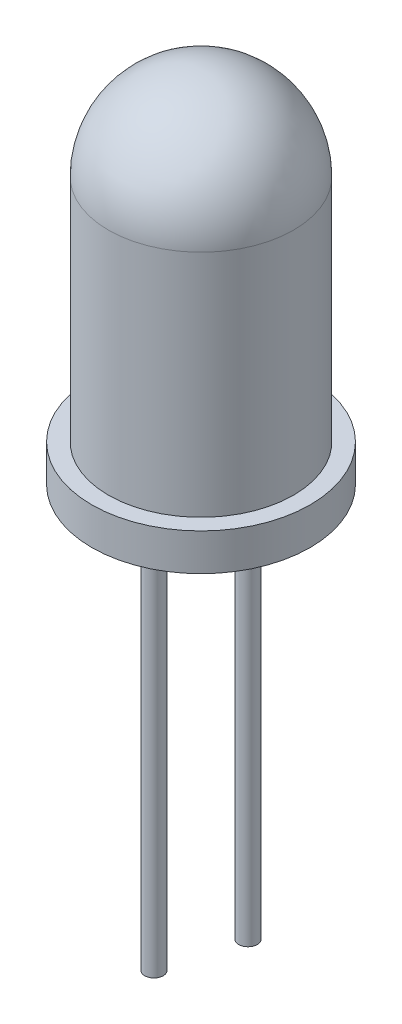
SolidWorks part; units mm, degrees
ref_plane "Front Plane" through (0, 0, 0) normal (0, 0, 1) x (1, 0, 0)
ref_plane "Top Plane" through (0, 0, 0) normal (0, 1, 0) x (1, 0, 0)
ref_plane "Right Plane" through (0, 0, 0) normal (1, 0, 0) x (0, 0, -1)
sketch "Sketch1" plane through (0, 0, 0) normal (0, 0, 1) x (1, 0, 0)
  line L0 (0, 0) -> (0, 9.7)
  line L1 (2.5, 7.2) -> (2.5, 1)
  line L2 (2.5, 1) -> (2.95, 1)
  line L3 (2.95, 1) -> (2.95, 0)
  line L4 (2.95, 0) -> (0, 0)
  arc A0 (0, 9.7) -> (2.5, 7.2) centre (0, 7.2) cw
  dimension "D1" = 2.5
  dimension "D2" = 8.7
  dimension "D3" = 2.95
  dimension "D4" = 1
revolve "Revolve1" add sketch "Sketch1" angle 360 about L0
sketch "Sketch2" plane through (0, 0, 0) normal (0, -1, 0) x (1, 0, 0)
  circle A0 centre (1.27, 0) radius 0.25
  dimension "D1" = 0.5
  dimension "D2" = 1.27
extrude "Boss-Extrude1" add sketch "Sketch2" along normal blind 10
sketch "Sketch3" plane through (0, 0, 0) normal (0, -1, 0) x (1, 0, 0)
  circle A0 centre (-1.27, 0) radius 0.25
  point P2 (-1.27, 0)
  dimension "D1" = 0.5
  dimension "D2" = 1.27
extrude "Boss-Extrude2" add sketch "Sketch3" along normal blind 12
